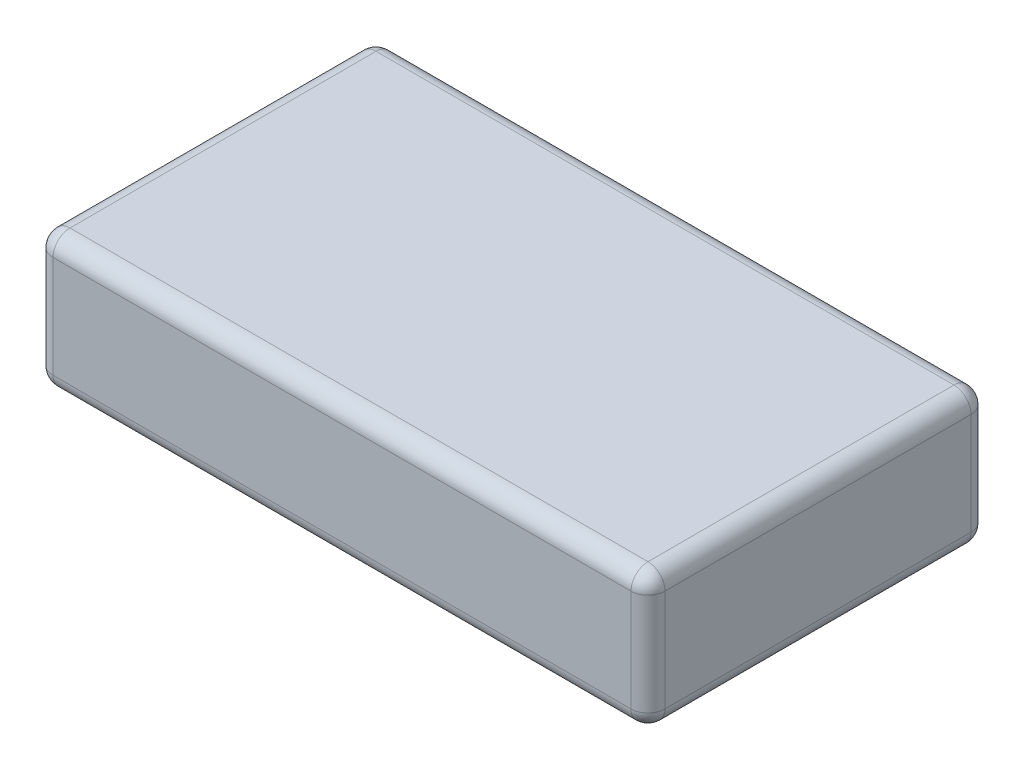
SolidWorks part; units mm, degrees
ref_plane "Front Plane" through (0, 0, 0) normal (0, 0, 1) x (1, 0, 0)
ref_plane "Top Plane" through (0, 0, 0) normal (0, 1, 0) x (1, 0, 0)
ref_plane "Right Plane" through (0, 0, 0) normal (1, 0, 0) x (0, 0, -1)
sketch "Sketch1" plane through (0, 0, 0) normal (0, 1, 0) x (1, 0, 0)
  line L1 (-28.575, -15.875) -> (28.575, -15.875)
  line L2 (-28.575, -15.875) -> (-28.575, 15.875)
  line L3 (-28.575, 15.875) -> (28.575, 15.875)
  line L4 (28.575, -15.875) -> (28.575, 15.875)
  point P4 (-28.575, 0)
  point P5 (0, 15.875)
  point P6 (0, 0)
  dimension "D1" = 57.15
  dimension "D2" = 31.75
extrude "Boss-Extrude1" add sketch "Sketch1" along normal blind 12.7
fillet "Fillet1" radius 1.5875 12 edges at (28.575, 6.35, -15.875) (28.575, 6.35, 15.875) (-28.575, 6.35, -15.875) (-28.575, 6.35, 15.875) (0, 0, 15.875) (28.575, 0, 0) (0, 0, -15.875) (-28.575, 0, 0) (0, 12.7, -15.875) (28.575, 12.7, 0) (0, 12.7, 15.875) (-28.575, 12.7, 0)
